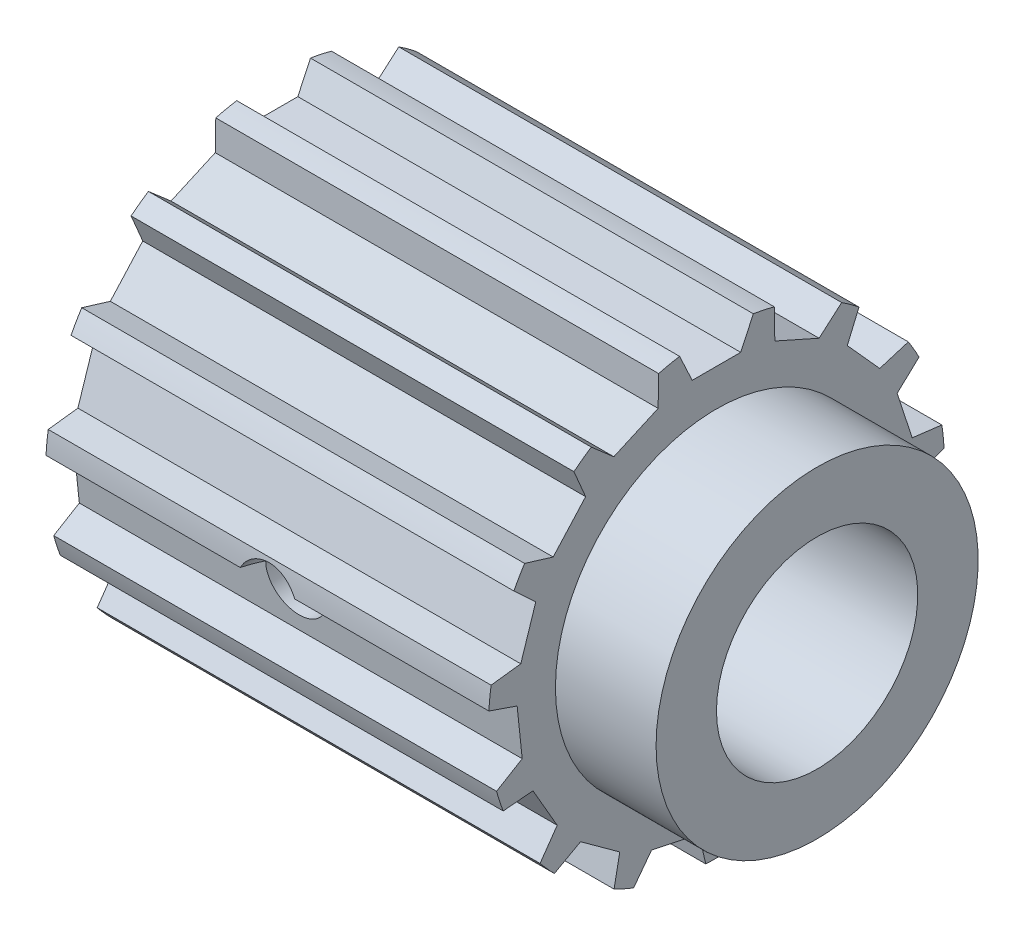
SolidWorks part; units mm, degrees
material "Alliage 1060"
ref_plane "Plan de face" through (0, 0, 0) normal (0, 0, 1) x (1, 0, 0)
ref_plane "Plan de dessus" through (0, 0, 0) normal (0, 1, 0) x (1, 0, 0)
ref_plane "Plan de droite" through (0, 0, 0) normal (1, 0, 0) x (0, 0, -1)
sketch "Esquisse1" plane through (0, 0, 0) normal (0, 0, 1) x (1, 0, 0)
  line L0 (-12.2548, 0) -> (24.5095, 0) construction
  line L1 (0, 5) -> (0, 8)
  line L2 (0, 8) -> (-5, 8)
  line L3 (-5, 8) -> (-5, 11.325)
  line L4 (-5, 11.325) -> (-27, 11.325)
  line L5 (-27, 11.325) -> (-27, 5)
  line L6 (-27, 5) -> (0, 5)
  dimension "D1" = 10
  dimension "D2" = 16
  dimension "D3" = 22.65
  dimension "D4" = 5
  dimension "D5" = 22
revolve "Révolution1" add sketch "Esquisse1" angle 360 about L0
sketch "Esquisse2" plane through (0, 0, 0) normal (0, 0, 1) x (1, 0, 0)
  circle A0 centre (-16, 0) radius 1.5
  dimension "D1" = 3
  dimension "D2" = 16
extrude "Enlèv. mat.-Extru.1" cut sketch "Esquisse2" against normal through all and the other way through all
sketch "Esquisse3" plane through (-27, 0, 0) normal (-1, 0, 0) x (0, 0, 1)
  line L0 (-2.16, 11.8802) -> (-1.2041, 9.8302)
  line L1 (-1.2041, 9.8302) -> (1.2041, 9.8302)
  line L2 (1.2041, 9.8302) -> (2.16, 11.8802)
  line L3 (0, 0) -> (0, 13.7521) construction
  arc A0 (-2.16, 11.8802) -> (2.16, 11.8802) centre (0, 0) cw
  dimension "D3" = 12.075
  dimension "D1" = 25
  dimension "D2" = 25
  dimension "D4" = 2.05
  dimension "D5" = 4.32
extrude "Enlèv. mat.-Extru.2" cut sketch "Esquisse3" against normal up to next
pattern_circular "Répétition circulaire1" count 15 every 24 about axis through (0, 0, 0) along (1, 0, 0) of "Enlèv. mat.-Extru.2"
